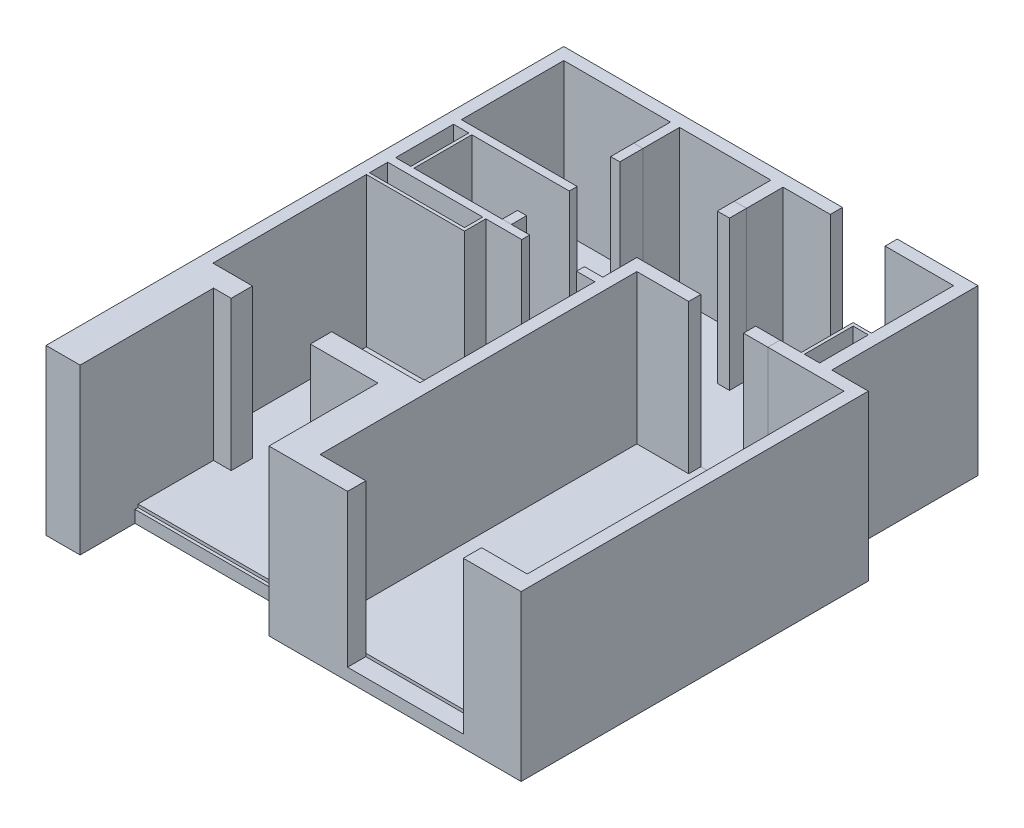
SolidWorks part; units mm, degrees
ref_plane "Спереди" through (0, 0, 0) normal (0, 0, 1) x (1, 0, 0)
ref_plane "Сверху" through (0, 0, 0) normal (0, 1, 0) x (1, 0, 0)
ref_plane "Справа" through (0, 0, 0) normal (1, 0, 0) x (0, 0, -1)
other "Configuration Table"
sketch "чертеж" plane through (0, 0, 0) normal (0, 1, 0) x (1, 0, 0)
  line L0 (-122.4645, -5934.5928) -> (200.8688, -5934.5928) construction
  line L1 (11.3792, -6202.3586) -> (334.7125, -6202.3586) construction
  line L2 (-29.7674, 42.6262) -> (294.8993, 42.6262) construction
  line L3 (-41.8231, 39.2884) -> (282.8435, 39.2884) construction
  line L4 (2418.4622, -1094.6493) -> (2743.1288, -1094.6493) construction
  line L5 (-60.4594, 42.9789) -> (264.2073, 42.9789) construction
  line L6 (-48.7728, 66.0913) -> (275.8939, 66.0913) construction
  line L7 (-42.5542, 93.9023) -> (282.1124, 93.9023) construction
  line L8 (134.2311, 87.3942) -> (458.8978, 87.3942) construction
  line L9 (-47.3906, 51.9395) -> (277.2761, 51.9395) construction
  line L10 (-66.0858, -48.647) -> (431.2475, -48.647) construction
sketch "Эскиз по чертежу" plane through (0, 0, 0) normal (0, 1, 0) x (1, 0, 0)
  line L0 (0, 0) -> (0, 8400) construction
  line L1 (0, 8400) -> (1925, 8400) construction
  line L2 (6600, 8400) -> (6600, 6000) construction
  line L4 (7200, 6000) -> (7200, 600) construction
  line L5 (7200, 600) -> (3600, 600) construction
  line L6 (3600, 600) -> (3600, 8400) construction
  line L7 (3600, 2400) -> (0, 2400) construction
  line L8 (3600, 5475) -> (0, 5475) construction
  line L32 (6600, 6000) -> (7200, 6000) construction
  line L33 (0, 900) -> (3600, 900) construction
  line L37 (0, 1050) -> (3600, 1050) construction
  line L40 (1925, 5475) -> (1925, 6550) construction
  line L42 (1925, 6550) -> (1925, 8400) construction
  line L45 (1925, 8400) -> (3600, 8400) construction
  line L46 (3600, 8400) -> (6600, 8400) construction
  line L49 (1925, 6550) -> (0, 6550) construction
  dimension "D1" = 600
  dimension "D2" = 1800
  dimension "D3" = 3600
  dimension "D4" = 1500
  dimension "D5" = 600
  dimension "D6" = 3600
  dimension "D7" = 3600
  dimension "D8" = 2400
  dimension "D9" = 2925
  dimension "D10" = 1925
  dimension "D11" = 1850
  dimension "D12" = 1350
sketch "Эскиз3" plane through (0, 0, 0) normal (0, 1, 0) x (1, 0, 0)
  line L0 (0, 0) -> (0, 8400) construction
  line L1 (7200, 6000) -> (7200, 600) construction
  line L3 (6600, 8400) -> (6600, 6000) construction
  line L11 (100, 8300) -> (3500, 8300)
  line L15 (3500, 8300) -> (3500, 7700)
  line L16 (3500, 7700) -> (3700, 7700)
  line L17 (3700, 7700) -> (3700, 8300)
  line L19 (0, 8400) -> (1925, 8400) construction
  line L20 (6500, 6100) -> (5850, 6100)
  line L21 (-100, 8500) -> (4475, 8500)
  line L22 (6500, 8300) -> (6500, 6100)
  line L24 (4475, 8500) -> (4475, 8300)
  line L25 (4475, 8300) -> (3700, 8300)
  line L26 (6700, 8500) -> (5375, 8500)
  line L29 (7100, 5900) -> (7100, 700)
  line L30 (4450, 700) -> (3700, 700)
  line L32 (6350, 500) -> (7300, 500)
  line L33 (7300, 500) -> (7300, 6100)
  line L34 (7300, 6100) -> (6700, 6100)
  line L35 (6700, 6100) -> (6700, 8500)
  line L39 (5375, 8500) -> (5375, 8300)
  line L40 (5375, 8300) -> (6500, 8300)
  line L41 (5850, 6100) -> (5850, 5900)
  line L42 (5850, 5900) -> (7100, 5900)
  line L45 (-100, 8500) -> (-100, 0)
  line L46 (-100, 0) -> (100, 0)
  line L47 (3500, 6100) -> (4550, 6100)
  line L52 (100, 0) -> (100, 8300)
  line L60 (3700, 700) -> (3700, 5900)
  line L68 (3500, 6100) -> (3500, 500)
  line L69 (4550, 6100) -> (4550, 5900)
  line L70 (4550, 5900) -> (3700, 5900)
  line L71 (7100, 700) -> (6350, 700)
  line L72 (6350, 500) -> (6350, 700)
  line L73 (3500, 500) -> (4450, 500)
  line L74 (4450, 500) -> (4450, 700)
  line L75 (7200, 600) -> (3600, 600) construction
  dimension "D1" = 3400
  dimension "D2" = 3400
  dimension "D3" = 5200
  dimension "D4" = 1300
  dimension "D5" = 200
  dimension "D6" = 2800
  dimension "D7" = 200
  dimension "D8" = 200
  dimension "D9" = 2200
  dimension "D10" = 100
  dimension "D11" = 100
  dimension "D12" = 100
  dimension "D13" = 200
  dimension "D14" = 100
  dimension "D15" = 900
  dimension "D16" = 100
  dimension "D17" = 1125
  dimension "D18" = 600
  dimension "D19" = 200
  dimension "D20" = 850
  dimension "D21" = 1900
  dimension "D22" = 750
extrude "несущие стены" add sketch "Эскиз3" along normal blind 2500 separate body
sketch "Эскиз5" plane through (0, 0, 0) normal (0, 1, 0) x (1, 0, 0)
  line L0 (100, 6620) -> (1850, 6620)
  line L2 (1850, 6620) -> (1850, 7000)
  line L3 (1850, 7000) -> (2000, 7000)
  line L4 (2000, 7000) -> (2000, 6240)
  line L5 (2000, 6240) -> (1850, 6240)
  line L6 (1850, 6240) -> (1850, 6490)
  line L7 (1850, 6490) -> (100, 6490)
  line L9 (100, 6490) -> (100, 6620)
  line L10 (100, 5410) -> (2300, 5410)
  line L12 (2300, 5410) -> (2300, 5540)
  line L17 (2300, 5540) -> (100, 5540)
  line L18 (100, 5540) -> (100, 5410)
  line L19 (3500, 5410) -> (3200, 5410)
  line L20 (3500, 6100) -> (3500, 500) construction
  line L21 (3200, 5410) -> (3200, 5540)
  line L22 (3200, 5540) -> (3500, 5540)
  line L23 (100, 0) -> (100, 8300) construction
  line L24 (3500, 5540) -> (3500, 5410)
  line L25 (1850, 8300) -> (1850, 7700)
  line L27 (1850, 7700) -> (2000, 7700)
  line L28 (2000, 7700) -> (2000, 8300)
  line L30 (2000, 8300) -> (1850, 8300)
  line L31 (100, 8300) -> (3500, 8300) construction
  line L32 (3500, 8300) -> (3500, 7700) construction
  point P34 (3200, 5475)
  dimension "D1" = 600
  dimension "D2" = 1750
  dimension "D3" = 1500
  dimension "D4" = 1680
  dimension "D5" = 130
  dimension "D6" = 700
  dimension "D7" = 700
  dimension "D8" = 950
  dimension "D9" = 900
  dimension "D10" = 300
  dimension "D11" = 150
  dimension "D12" = 130
extrude "перегородки санузла" add sketch "Эскиз5" along normal up to surface (2500 mm away) up to face at (2335, 2500, -6560)
sketch "Эскиз7" plane through (0, 0, 0) normal (0, 1, 0) x (1, 0, 0)
  line L0 (100, 0) -> (100, 5410) construction
  line L1 (750, 2540) -> (100, 2540)
  line L2 (460, 2190) -> (460, 0)
  line L3 (3160, 2190) -> (3160, 400)
  line L4 (3160, 400) -> (4450, 400)
  line L5 (460, 0) -> (100, 0)
  line L6 (100, 2540) -> (100, 0)
  line L7 (3200, 5410) -> (3500, 5410) construction
  line L8 (3160, 2190) -> (2050, 2190)
  line L9 (3500, 500) -> (4450, 500) construction
  line L10 (2050, 2540) -> (3500, 2540)
  line L14 (3500, 5410) -> (3500, 500) construction
  line L19 (4450, 500) -> (4450, 400)
  line L20 (6350, 500) -> (7300, 500)
  line L21 (6350, 500) -> (6350, 400)
  line L22 (6350, 400) -> (7300, 400)
  line L23 (7300, 500) -> (7300, 400)
  line L24 (2050, 2190) -> (2050, 2540)
  line L25 (3500, 2540) -> (3500, 500)
  line L26 (3500, 500) -> (4450, 500)
  line L27 (3500, 5410) -> (3500, 500) construction
  line L28 (6350, 500) -> (7300, 500) construction
  line L29 (460, 2190) -> (750, 2190)
  line L30 (750, 2190) -> (750, 2540)
  line L31 (4450, 500) -> (4450, 700) construction
  line L32 (6350, 700) -> (6350, 500) construction
  dimension "D1" = 2700
  dimension "D2" = 100
  dimension "D3" = 350
  dimension "D4" = 1450
  dimension "D5" = 1300
  dimension "D6" = 1110
  dimension "D7" = 2870
extrude "лоджия" add sketch "Эскиз7" along normal up to surface (2500 mm away) contours L10 | L19 L4 L3 L10 L25 L26 | L22 L23 L20 L21
sketch "Эскиз8" plane through (0, 0, 0) normal (0, 1, 0) x (1, 0, 0)
  line L1 (50, 5460) -> (1710, 5460)
  line L2 (50, 5460) -> (50, 5060)
  line L3 (50, 5060) -> (1710, 5060)
  line L4 (1710, 5460) -> (1710, 5060)
  line L5 (100, 5410) -> (1660, 5410)
  line L6 (100, 5410) -> (100, 5110)
  line L7 (100, 5110) -> (1660, 5110)
  line L8 (1660, 5410) -> (1660, 5110)
  line L9 (100, 5410) -> (2300, 5410) construction
  line L10 (100, 2540) -> (100, 5410) construction
  dimension "D1" = 350
  dimension "D2" = 50
  dimension "D3" = 50
  dimension "D4" = 50
  dimension "D5" = 1610
  dimension "D6" = 50
extrude "вытяжка кухня" add sketch "Эскиз8" along normal up to surface (2500 mm away) up to face at (6453.5714, 2500, -5142.8571)
sketch "Эскиз9" plane through (0, 0, 0) normal (0, 1, 0) x (1, 0, 0)
  line L1 (6550, 6950) -> (6200, 6950)
  line L2 (6550, 6950) -> (6550, 6050)
  line L3 (6550, 6050) -> (6200, 6050)
  line L4 (6200, 6950) -> (6200, 6050)
  line L6 (6500, 6100) -> (5850, 6100) construction
  line L7 (6250, 6900) -> (6500, 6900)
  line L8 (6250, 6900) -> (6250, 6100)
  line L9 (6250, 6100) -> (6500, 6100)
  line L10 (6500, 6900) -> (6500, 6100)
  line L11 (6500, 8300) -> (6500, 6100) construction
  line L12 (50, 6540) -> (400, 6540)
  line L14 (400, 6540) -> (400, 5490)
  line L16 (400, 5490) -> (50, 5490)
  line L17 (50, 5490) -> (50, 6540)
  line L18 (100, 6490) -> (350, 6490)
  line L19 (350, 6490) -> (350, 5540)
  line L20 (350, 5540) -> (100, 5540)
  line L21 (100, 5540) -> (100, 6490)
  line L22 (1850, 6490) -> (1850, 6240) construction
  line L23 (100, 6490) -> (1850, 6490) construction
  point P13 (6375, 6950)
  dimension "D1" = 850
  dimension "D2" = 50
  dimension "D3" = 50
  dimension "D4" = 300
  dimension "D5" = 50
  dimension "D6" = 50
  dimension "D7" = 50
  dimension "D8" = 50
  dimension "D9" = 50
  dimension "D10" = 50
  dimension "D11" = 1450
extrude "зсс" add sketch "Эскиз9" along normal up to surface (2500 mm away) up to face at (6453.5714, 2500, -5142.8571)
sketch "Эскиз11" plane through (0, 0, 0) normal (0, 1, 0) x (1, 0, 0)
  line L1 (2050, 2540) -> (1450, 2540)
  line L2 (2050, 2540) -> (2050, 2190)
  line L3 (2050, 2190) -> (1450, 2190)
  line L4 (1450, 2540) -> (1450, 2190)
  line L5 (750, 2190) -> (750, 2540) construction
  dimension "D1" = 700
extrude "лоджияперегородка" add sketch "Эскиз11" along normal blind 600
sketch "Эскиз4" plane through (0, 0, 0) normal (0, 1, 0) x (1, 0, 0)
  line L8 (-100, 8500) -> (6700, 8500)
  line L9 (6700, 8500) -> (6700, 6100)
  line L10 (6700, 6100) -> (7300, 6100)
  line L11 (7300, 6100) -> (7300, 400)
  line L13 (3160, 400) -> (3160, 900)
  line L14 (3160, 900) -> (460, 900)
  line L17 (-100, 0) -> (-100, 8500)
  line L18 (6700, 6100) -> (6700, 8500) construction
  line L19 (6700, 8500) -> (5375, 8500) construction
  line L23 (0, 900) -> (3600, 900) construction
  line L24 (460, 900) -> (460, 0)
  line L25 (460, 0) -> (-100, 0)
  line L26 (3160, 400) -> (7300, 400)
  line L27 (3160, 2190) -> (3160, 400) construction
  line L28 (460, 0) -> (460, 2190) construction
  line L29 (-100, 0) -> (460, 0) construction
extrude "пол" add sketch "Эскиз4" against normal blind 200
sketch "Эскиз что надо" plane through (0, 0, 0) normal (0, 1, 0) x (1, 0, 0)
  line L0 (5525, 8300) -> (5525, 6100) construction
  line L5 (2000, 6240) -> (2000, 7000) construction
  line L6 (1850, 7000) -> (2000, 7000)
  line L7 (1850, 7000) -> (1850, 6620)
  line L8 (1850, 6620) -> (2000, 6620)
  line L9 (2000, 7000) -> (2000, 6620)
  line L10 (1850, 6490) -> (1850, 6240) construction
  line L11 (1850, 7700) -> (2000, 7700)
  line L12 (1850, 7700) -> (1850, 7320)
  line L13 (1850, 7320) -> (2000, 7320)
  line L14 (2000, 7700) -> (2000, 7320)
  line L15 (1850, 5540) -> (2000, 5540)
  line L16 (1850, 5540) -> (1850, 5790)
  line L17 (1850, 5790) -> (2000, 5790)
  line L18 (2000, 5540) -> (2000, 5790)
  line L19 (1850, 6490) -> (2000, 6490)
  line L20 (1850, 6490) -> (1850, 6240)
  line L21 (1850, 6240) -> (2000, 6240)
  line L22 (2000, 6490) -> (2000, 6240)
  line L23 (1850, 7000) -> (1850, 6620) construction
  line L28 (3500, 7700) -> (3700, 7700) construction
  line L29 (3500, 7700) -> (3500, 7420) construction
  line L30 (3500, 7420) -> (3700, 7420) construction
  line L31 (3700, 7700) -> (3700, 7420) construction
  line L32 (4550, 5900) -> (4550, 6100) construction
  line L35 (5850, 5900) -> (5450, 5900)
  line L36 (5850, 5900) -> (5850, 6100)
  line L37 (5850, 6100) -> (5450, 6100)
  line L38 (5450, 5900) -> (5450, 6100)
  line L39 (5375, 8300) -> (6500, 8300) construction
  line L40 (2000, 7420) -> (3500, 7420) construction
  line L41 (5375, 8500) -> (5375, 8300) construction
  line L42 (2300, 5540) -> (400, 5540) construction
  line L43 (1450, 2540) -> (2050, 2540)
  line L44 (1450, 2540) -> (1450, 2190)
  line L46 (1450, 2190) -> (2050, 2190)
  line L47 (2000, 7320) -> (2000, 6620) construction
  line L48 (2050, 2540) -> (2050, 2190)
  point P32 (1925, 6490)
  dimension "D8" = 900
  dimension "D1" = 700
  dimension "D2" = 700
  dimension "D3" = 150
  dimension "D5" = 100
sketch "Эскиз13" plane through (0, 0, 0) normal (0, 1, 0) x (1, 0, 0)
  line L1 (1850, 6490) -> (2000, 6490)
  line L2 (1850, 6490) -> (1850, 6240)
  line L3 (1850, 6240) -> (2000, 6240)
  line L4 (2000, 6490) -> (2000, 6240)
  line L5 (1850, 7000) -> (2000, 7000)
  line L6 (1850, 7000) -> (1850, 6620)
  line L7 (1850, 6620) -> (2000, 6620)
  line L8 (2000, 7000) -> (2000, 6620)
  line L9 (1450, 2540) -> (2050, 2540)
  line L10 (1450, 2540) -> (1450, 2190)
  line L11 (1450, 2190) -> (2050, 2190)
  line L12 (2050, 2540) -> (2050, 2190)
extrude "санузел вырез" cut sketch "Эскиз13" along normal through all
sketch "Эскиз14" plane through (0, 0, 0) normal (0, 1, 0) x (1, 0, 0)
  line L1 (5850, 6100) -> (5450, 6100)
  line L2 (5850, 6100) -> (5850, 5900)
  line L3 (5850, 5900) -> (5450, 5900)
  line L4 (5450, 6100) -> (5450, 5900)
  line L5 (1850, 5540) -> (2000, 5540)
  line L6 (1850, 5540) -> (1850, 5790)
  line L7 (1850, 5790) -> (2000, 5790)
  line L8 (2000, 5540) -> (2000, 5790)
  line L9 (1850, 7700) -> (2000, 7700)
  line L10 (1850, 7700) -> (1850, 7320)
  line L11 (1850, 7320) -> (2000, 7320)
  line L12 (2000, 7700) -> (2000, 7320)
extrude "наращивание стен" add sketch "Эскиз14" along normal through all separate body
sketch "Эскиз15" plane through (0, 0, 0) normal (0, 1, 0) x (1, 0, 0)
  line L12 (3700, 7700) -> (3500, 7700) construction
  line L29 (3700, 7420) -> (3700, 7700)
  line L30 (3700, 7700) -> (3500, 7700)
  line L32 (3500, 7700) -> (3500, 7420)
  line L36 (3500, 7420) -> (3700, 7420)
  line L39 (3500, 7700) -> (3500, 7420) construction
  line L40 (3700, 7700) -> (3700, 7420) construction
  line L46 (3500, 7700) -> (3700, 7700) construction
  line L47 (2000, 7420) -> (2800, 7420) construction
  line L48 (2000, 7420) -> (2000, 7500) construction
  line L49 (2000, 7500) -> (2800, 7500) construction
  line L50 (2800, 7420) -> (2800, 7500) construction
  dimension "D1" = 80
  dimension "D2" = 700
extrude "наращивание стен 2" add sketch "Эскиз15" along normal through all separate body
sketch "Эскиз37" plane through (0, 0, 0) normal (0, 1, 0) x (1, 0, 0)
  line L0 (3700, 700) -> (7100, 700)
  line L1 (7100, 700) -> (7100, 5900)
  line L2 (7100, 5900) -> (5850, 5900)
  line L3 (5850, 5900) -> (5850, 6100)
  line L7 (5850, 6100) -> (4550, 6100)
  line L8 (4550, 6100) -> (4550, 5900)
  line L9 (4550, 5900) -> (3700, 5900)
  line L10 (3700, 5900) -> (3700, 700)
extrude "зал" add sketch "Эскиз37" along normal blind 50 separate body
sketch "Эскиз38" plane through (0, 0, 0) normal (0, 1, 0) x (1, 0, 0)
  line L0 (460, 950) -> (3160, 950)
  line L1 (3160, 950) -> (3160, 2190)
  line L2 (3160, 2190) -> (2050, 2190)
  line L3 (2050, 2190) -> (2050, 2540)
  line L4 (2050, 2540) -> (3500, 2540)
  line L5 (3500, 5410) -> (3500, 2540) construction
  line L6 (3500, 2540) -> (3500, 5410)
  line L7 (3500, 5410) -> (3200, 5410)
  line L8 (3200, 5410) -> (3200, 5540)
  line L9 (3200, 5540) -> (2300, 5540)
  line L10 (2300, 5540) -> (2300, 5410)
  line L11 (2300, 5410) -> (1710, 5410)
  line L12 (1710, 5410) -> (1710, 5060)
  line L13 (1710, 5060) -> (100, 5060)
  line L14 (100, 5060) -> (100, 2540)
  line L15 (100, 2540) -> (750, 2540)
  line L16 (750, 2540) -> (750, 2190)
  line L17 (750, 2190) -> (460, 2190)
  line L18 (460, 2190) -> (460, 950)
  line L19 (460, 0) -> (460, 2190) construction
  line L20 (460, 900) -> (3160, 900) construction
  dimension "D1" = 50
extrude "кухня лоджия" add sketch "Эскиз38" along normal blind 50 separate body
sketch "Эскиз40" plane through (0, 0, 0) normal (0, 1, 0) x (1, 0, 0)
  line L0 (6200, 6100) -> (6200, 6950)
  line L1 (6200, 6950) -> (6500, 6950)
  line L2 (6500, 6950) -> (6500, 8300)
  line L3 (6500, 8300) -> (3700, 8300)
  line L4 (3700, 8300) -> (3700, 7420)
  line L5 (3700, 7420) -> (3500, 7420)
  line L6 (3500, 7420) -> (3500, 8300)
  line L7 (3500, 8300) -> (2000, 8300)
  line L8 (2000, 8300) -> (2000, 5540)
  line L9 (2000, 5540) -> (3500, 5540)
  line L10 (3500, 5540) -> (3500, 6100)
  line L11 (3500, 6100) -> (6200, 6100)
extrude "прихожия" add sketch "Эскиз40" along normal blind 50 separate body
sketch "Эскиз42" plane through (0, 0, 0) normal (0, 1, 0) x (1, 0, 0)
  line L0 (100, 8300) -> (100, 6620)
  line L1 (100, 6620) -> (2000, 6620)
  line L4 (2000, 6620) -> (2000, 7320)
  line L5 (2000, 7320) -> (1850, 7320)
  line L6 (1850, 7320) -> (1850, 8300)
  line L7 (1850, 8300) -> (100, 8300)
  line L8 (2000, 8300) -> (2000, 5540) construction
  line L9 (2000, 6620) -> (100, 6620) construction
  line L10 (2000, 8300) -> (2000, 5540) construction
extrude "ванная" add sketch "Эскиз42" along normal blind 50 separate body
sketch "Эскиз45" plane through (0, 50, 0) normal (0, 1, 0) x (1, 0, 0)
  line L0 (400, 6490) -> (2000, 6490) construction
  line L1 (850, 6490) -> (930, 6490)
  line L2 (850, 6490) -> (850, 5540)
  line L3 (850, 5540) -> (930, 5540)
  line L4 (930, 6490) -> (930, 5540)
  line L5 (2300, 5540) -> (400, 5540) construction
  line L7 (1850, 5790) -> (1850, 5540) construction
  dimension "D1" = 80
  dimension "D2" = 920
extrude "Бобышка-Вытянуть33" add sketch "Эскиз45" along normal blind 1200 separate body
sketch "Эскиз46" plane through (930, 0, 0) normal (1, 0, 0) x (0, 0, -1)
  line L0 (5540, 50) -> (6490, 50) construction
  line L1 (5835, 440) -> (6195, 440)
  line L2 (5835, 440) -> (5835, 80)
  line L3 (5835, 80) -> (6195, 80)
  line L4 (6195, 440) -> (6195, 80)
  line L6 (6015, 50) -> (6015, 440) construction
  line L7 (6490, 1250) -> (6490, 50) construction
  line L8 (6015, 440) -> (6015, 950) construction
  line L9 (5940, 1040) -> (6090, 1040)
  line L10 (5940, 1040) -> (5940, 950)
  line L11 (5940, 950) -> (6090, 950)
  line L12 (6090, 1040) -> (6090, 950)
  line L14 (6280, 550) -> (6480, 550)
  line L15 (6280, 550) -> (6280, 50)
  line L16 (6280, 50) -> (6480, 50)
  line L17 (6480, 550) -> (6480, 50)
  point P4 (6015, 50)
  dimension "D1" = 360
  dimension "D2" = 390
  dimension "D3" = 150
  dimension "D4" = 90
  dimension "D5" = 900
  dimension "D6" = 30
  dimension "D7" = 200
  dimension "D8" = 500
  dimension "D9" = 10
extrude "Вырез-Вытянуть2" cut sketch "Эскиз46" against normal up to surface (80 mm away) up to face at (850, 650, -6015)
sketch "Эскиз43" plane through (0, 0, 0) normal (0, 1, 0) x (1, 0, 0)
  line L0 (930, 6490) -> (930, 5540)
  line L1 (930, 5540) -> (1850, 5540)
  line L2 (2300, 5540) -> (400, 5540) construction
  line L3 (1850, 5540) -> (1850, 5790)
  line L4 (1850, 5790) -> (2000, 5790)
  line L5 (2000, 5790) -> (2000, 6490)
  line L8 (2000, 6490) -> (930, 6490)
extrude "толчок" add sketch "Эскиз43" along normal blind 50 separate body
